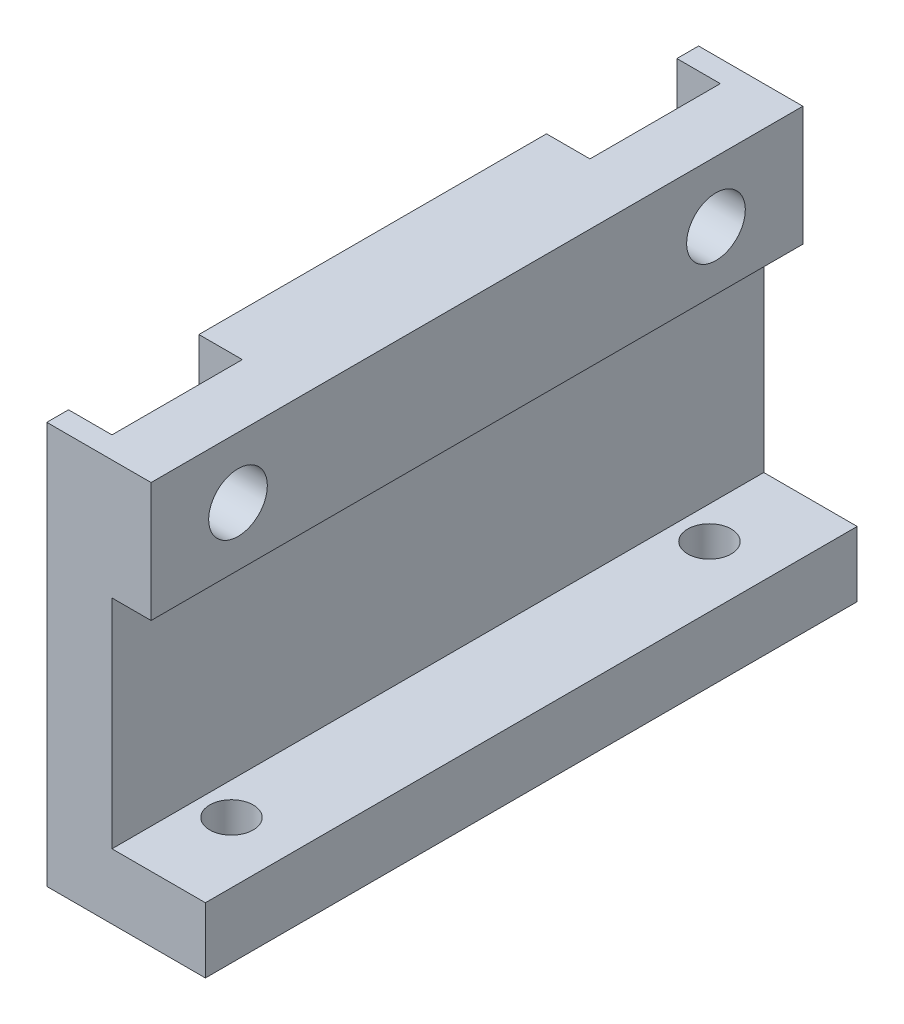
SolidWorks part; units mm, degrees
ref_plane "前视基准面" through (0, 0, 0) normal (0, 0, 1) x (1, 0, 0)
ref_plane "上视基准面" through (0, 0, 0) normal (0, 1, 0) x (1, 0, 0)
ref_plane "右视基准面" through (0, 0, 0) normal (1, 0, 0) x (0, 0, -1)
sketch "草图1" plane through (0, 0, 0) normal (0, 0, 1) x (1, 0, 0)
  line L0 (0, 0) -> (7.3, 0)
  line L1 (7.3, 0) -> (7.3, 3)
  line L2 (7.3, 3) -> (3, 3)
  line L3 (3, 3) -> (3, 13)
  line L4 (4.8, 18.5) -> (0, 18.5)
  line L5 (0, 18.5) -> (0, 0)
  line L7 (4.8, 18.5) -> (4.8, 13)
  line L8 (4.8, 13) -> (3, 13)
  dimension "D1" = 1.8
  dimension "D2" = 4.3
  dimension "D3" = 18.5
  dimension "D4" = 3
  dimension "D6" = 5.5
  dimension "D7" = 3
extrude "凸台-拉伸1" add sketch "草图1" along normal blind 30
sketch "草图2" plane through (0, 0, 0) normal (0, -1, 0) x (1, 0, 0)
  line L0 (0, 15) -> (7.3, 15) construction
  line L1 (0, 30) -> (0, 0) construction
  line L2 (7.3, 30) -> (7.3, 0) construction
  circle A0 centre (4.5, 26) radius 1
  circle A1 centre (4.5, 4) radius 1
  dimension "D1" = 2
  dimension "D2" = 2.8
  dimension "D3" = 11
extrude "切除-拉伸1" cut sketch "草图2" against normal up to next
sketch "草图3" plane through (0, 0, 0) normal (-1, 0, 0) x (0, 0, 1)
  line L0 (15, 18.5) -> (15, 0) construction
  line L1 (30, 18.5) -> (0, 18.5) construction
  line L2 (30, 0) -> (0, 0) construction
  circle A0 centre (4, 15.7) radius 1.35
  circle A1 centre (26, 15.7) radius 1.35
  dimension "D2" = 2.7
  dimension "D1" = 11
  dimension "D3" = 2.8
extrude "切除-拉伸2" cut sketch "草图3" against normal up to next
sketch "草图4" plane through (0, 0, 0) normal (-1, 0, 0) x (0, 0, 1)
  line L0 (1, 15.7) -> (1, 18.7)
  line L2 (7, 15.7) -> (7, 18.7)
  line L3 (7, 18.7) -> (1, 18.7)
  line L4 (23, 15.7) -> (23, 20.0069)
  line L5 (23, 20.0069) -> (29, 20.0069)
  line L6 (29, 20.0069) -> (29, 15.7)
  arc A0 (1, 15.7) -> (7, 15.7) centre (4, 15.7) ccw
  arc A1 (23, 15.7) -> (29, 15.7) centre (26, 15.7) ccw
  dimension "D1" = 6
  dimension "D2" = 6
extrude "切除-拉伸3" cut sketch "草图4" against normal blind 2
